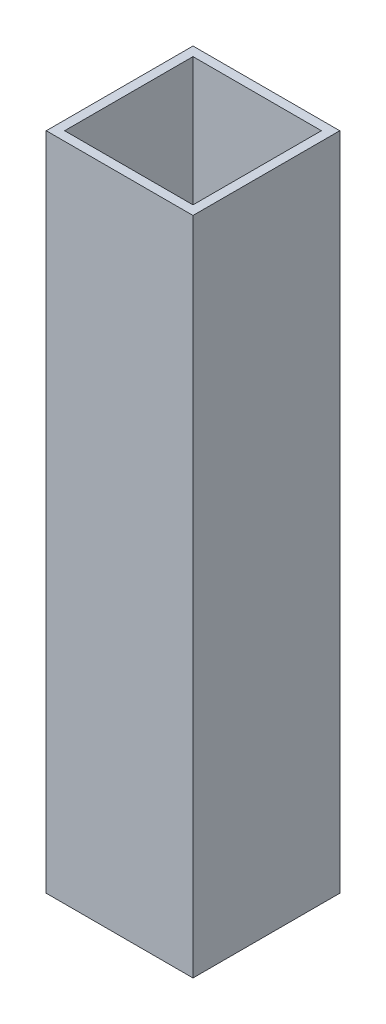
SolidWorks part; units mm, degrees
ref_plane "Front Plane" through (0, 0, 0) normal (0, 0, 1) x (1, 0, 0)
ref_plane "Top Plane" through (0, 0, 0) normal (0, 1, 0) x (1, 0, 0)
ref_plane "Right Plane" through (0, 0, 0) normal (1, 0, 0) x (0, 0, -1)
sketch "Sketch1" plane through (0, 0, 0) normal (0, 1, 0) x (1, 0, 0)
  line L1 (12.7, 12.7) -> (-12.7, 12.7)
  line L2 (12.7, 12.7) -> (12.7, -12.7)
  line L3 (12.7, -12.7) -> (-12.7, -12.7)
  line L4 (-12.7, 12.7) -> (-12.7, -12.7)
  line L5 (12.7, 12.7) -> (-12.7, -12.7) construction
  line L6 (12.7, -12.7) -> (-12.7, 12.7) construction
  line L7 (11.1125, 11.1125) -> (-11.1125, 11.1125)
  line L8 (11.1125, 11.1125) -> (11.1125, -11.1125)
  line L9 (11.1125, -11.1125) -> (-11.1125, -11.1125)
  line L10 (-11.1125, 11.1125) -> (-11.1125, -11.1125)
  line L11 (11.1125, 11.1125) -> (-11.1125, -11.1125) construction
  line L12 (11.1125, -11.1125) -> (-11.1125, 11.1125) construction
  point P0 (0, 0)
  point P6 (0, 0)
  dimension "D1" = 25.4
  dimension "D2" = 25.4
  dimension "D3" = 1.5875
  dimension "D4" = 1.5875
extrude "Boss-Extrude1" add sketch "Sketch1" along normal blind 114.3
